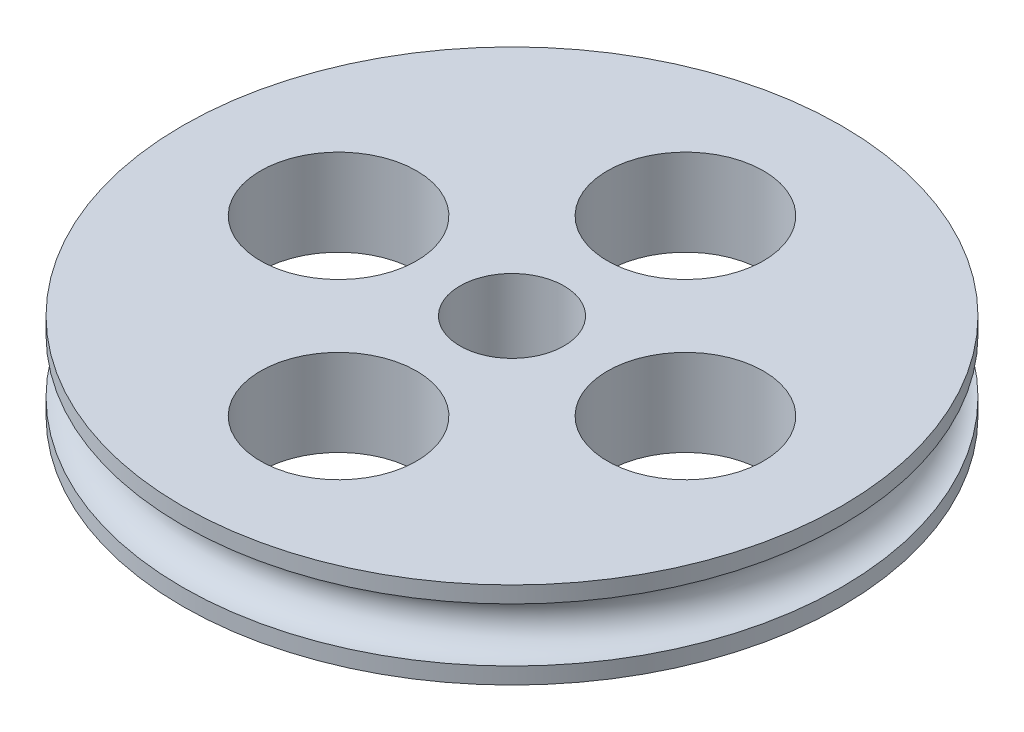
SolidWorks part; units mm, degrees
ref_plane "Plan de face" through (0, 0, 0) normal (0, 0, 1) x (1, 0, 0)
ref_plane "Plan de dessus" through (0, 0, 0) normal (0, 1, 0) x (1, 0, 0)
ref_plane "Plan de droite" through (0, 0, 0) normal (1, 0, 0) x (0, 0, -1)
sketch "Esquisse1" plane through (0, 0, 0) normal (0, 0, 1) x (1, 0, 0)
  line L0 (0, 0) -> (0, 41.0787) construction
  line L1 (-19, 0) -> (-3, 0)
  line L2 (-19, 0) -> (-19, 0.95)
  line L3 (-19, 4.05) -> (-19, 5)
  line L4 (-19, 5) -> (-3, 5)
  line L5 (-3, 5) -> (-3, 0)
  arc A0 (-19, 0.95) -> (-19, 4.05) centre (-19, 2.5) ccw
  dimension "D4" = 1.55
  dimension "D1" = 19
  dimension "D2" = 5
  dimension "D3" = 3
revolve "Révolution1" add sketch "Esquisse1" angle 360 about L0
sketch "Esquisse2" plane through (0, 0, 0) normal (0, -1, 0) x (-1, 0, 0)
  circle A0 centre (0, -10) radius 4.5
  circle A1 centre (-10, 0) radius 4.5
  circle A2 centre (0, 10) radius 4.5
  circle A3 centre (10, 0) radius 4.5
  point P12 (0, 0)
  dimension "D2" = 9
  dimension "D1" = 10
  dimension "D3" = 4
extrude "Enlèv. mat.-Extru.1" cut sketch "Esquisse2" against normal through all
